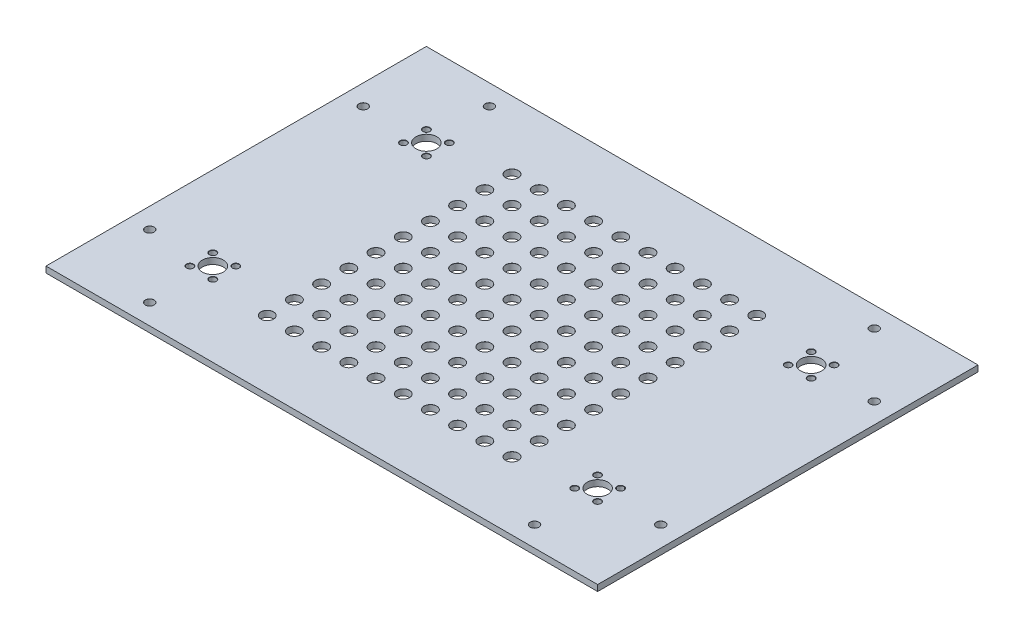
SolidWorks part; units mm, degrees
ref_plane "Front Plane" through (0, 0, 0) normal (0, 0, 1) x (1, 0, 0)
ref_plane "Top Plane" through (0, 0, 0) normal (0, 1, 0) x (1, 0, 0)
ref_plane "Right Plane" through (0, 0, 0) normal (1, 0, 0) x (0, 0, -1)
sketch "Sketch1" plane through (0, 0, 0) normal (0, 1, 0) x (1, 0, 0)
  line L0 (-115.9, 93.7) -> (-115.9, -93.7) construction
  line L1 (-135.9, -93.7) -> (135.9, -93.7)
  line L2 (-135.9, -93.7) -> (-135.9, 93.7)
  line L3 (-135.9, 93.7) -> (135.9, 93.7)
  line L4 (135.9, -93.7) -> (135.9, 93.7)
  line L5 (-135.9, -93.7) -> (135.9, 93.7) construction
  line L6 (-135.9, 93.7) -> (135.9, -93.7) construction
  line L7 (-94.8, -52.6) -> (94.8, -52.6) construction
  line L8 (-94.8, -52.6) -> (-94.8, 52.6) construction
  line L9 (-94.8, 52.6) -> (94.8, 52.6) construction
  line L10 (94.8, -52.6) -> (94.8, 52.6) construction
  line L11 (-94.8, -52.6) -> (94.8, 52.6) construction
  line L12 (-94.8, 52.6) -> (94.8, -52.6) construction
  line L13 (-115.9, 73.7) -> (-73.7, 73.7) construction
  line L14 (-115.9, 73.7) -> (-115.9, 31.5) construction
  line L15 (-115.9, 31.5) -> (-73.7, 31.5) construction
  line L16 (-73.7, 73.7) -> (-73.7, 31.5) construction
  line L17 (-115.9, 73.7) -> (-73.7, 31.5) construction
  line L18 (-115.9, 31.5) -> (-73.7, 73.7) construction
  line L19 (-115.9, 73.7) -> (135.9, 73.7) construction
  line L20 (-135.9, 73.7) -> (-115.9, 73.7) construction
  line L21 (-94.8, 73.7) -> (-94.8, 93.7) construction
  line L22 (-115.9, 52.6) -> (-135.9, 52.6) construction
  line L23 (-60.3, 93.7) -> (-60.3, -93.7) construction
  line L24 (-115.9, -73.7) -> (-73.7, -73.7) construction
  line L25 (-115.9, -73.7) -> (-115.9, -31.5) construction
  line L26 (-115.9, -31.5) -> (-73.7, -31.5) construction
  line L27 (-73.7, -73.7) -> (-73.7, -31.5) construction
  line L28 (-115.9, -73.7) -> (-73.7, -31.5) construction
  line L29 (-115.9, -31.5) -> (-73.7, -73.7) construction
  line L30 (73.7, 73.7) -> (115.9, 73.7) construction
  line L31 (73.7, 73.7) -> (73.7, 31.5) construction
  line L32 (73.7, 31.5) -> (115.9, 31.5) construction
  line L33 (115.9, 73.7) -> (115.9, 31.5) construction
  line L34 (73.7, 73.7) -> (115.9, 31.5) construction
  line L35 (73.7, 31.5) -> (115.9, 73.7) construction
  line L36 (73.7, -31.5) -> (115.9, -31.5) construction
  line L37 (73.7, -31.5) -> (73.7, -73.7) construction
  line L38 (73.7, -73.7) -> (115.9, -73.7) construction
  line L39 (115.9, -31.5) -> (115.9, -73.7) construction
  line L40 (73.7, -31.5) -> (115.9, -73.7) construction
  line L41 (73.7, -73.7) -> (115.9, -31.5) construction
  line L42 (-60.3, 60.3) -> (-60.3, 46.9) construction
  line L43 (-60.3, 60.3) -> (-46.9, 60.3) construction
  circle A0 centre (-94.8, 52.6) radius 5.15
  circle A1 centre (-94.8, -52.6) radius 5.15
  circle A2 centre (94.8, -52.6) radius 5.15
  circle A3 centre (94.8, 52.6) radius 5.15
  circle A4 centre (-60.3, 60.3) radius 1.6 construction
  point P0 (0, 0)
  point P6 (0, 0)
  point P37 (-60.3, 46.9)
  point P39 (-60.3, 60.3)
  point P40 (-60.3, 33.5)
  point P41 (-60.3, 20.1)
  point P42 (-60.3, 6.7)
  point P43 (-60.3, -6.7)
  point P44 (-60.3, -20.1)
  point P45 (-60.3, -33.5)
  point P46 (-60.3, -46.9)
  point P47 (-60.3, -60.3)
  point P53 (-46.9, 60.3)
  point P54 (-46.9, 46.9)
  point P55 (-46.9, 33.5)
  point P56 (-46.9, 20.1)
  point P57 (-46.9, 6.7)
  point P58 (-46.9, -6.7)
  point P59 (-46.9, -20.1)
  point P60 (-46.9, -33.5)
  point P61 (-46.9, -46.9)
  point P62 (-46.9, -60.3)
  point P63 (-33.5, 60.3)
  point P64 (-33.5, 46.9)
  point P65 (-33.5, 33.5)
  point P66 (-33.5, 20.1)
  point P67 (-33.5, 6.7)
  point P68 (-33.5, -6.7)
  point P69 (-33.5, -20.1)
  point P70 (-33.5, -33.5)
  point P71 (-33.5, -46.9)
  point P72 (-33.5, -60.3)
  point P73 (-20.1, 60.3)
  point P74 (-20.1, 46.9)
  point P75 (-20.1, 33.5)
  point P76 (-20.1, 20.1)
  point P77 (-20.1, 6.7)
  point P78 (-20.1, -6.7)
  point P79 (-20.1, -20.1)
  point P80 (-20.1, -33.5)
  point P81 (-20.1, -46.9)
  point P82 (-20.1, -60.3)
  point P83 (-6.7, 60.3)
  point P84 (-6.7, 46.9)
  point P85 (-6.7, 33.5)
  point P86 (-6.7, 20.1)
  point P87 (-6.7, 6.7)
  point P88 (-6.7, -6.7)
  point P89 (-6.7, -20.1)
  point P90 (-6.7, -33.5)
  point P91 (-6.7, -46.9)
  point P92 (-6.7, -60.3)
  point P93 (6.7, 60.3)
  point P94 (6.7, 46.9)
  point P95 (6.7, 33.5)
  point P96 (6.7, 20.1)
  point P97 (6.7, 6.7)
  point P98 (6.7, -6.7)
  point P99 (6.7, -20.1)
  point P100 (6.7, -33.5)
  point P101 (6.7, -46.9)
  point P102 (6.7, -60.3)
  point P103 (20.1, 60.3)
  point P104 (20.1, 46.9)
  point P105 (20.1, 33.5)
  point P106 (20.1, 20.1)
  point P107 (20.1, 6.7)
  point P108 (20.1, -6.7)
  point P109 (20.1, -20.1)
  point P110 (20.1, -33.5)
  point P111 (20.1, -46.9)
  point P112 (20.1, -60.3)
  point P113 (33.5, 60.3)
  point P114 (33.5, 46.9)
  point P115 (33.5, 33.5)
  point P116 (33.5, 20.1)
  point P117 (33.5, 6.7)
  point P118 (33.5, -6.7)
  point P119 (33.5, -20.1)
  point P120 (33.5, -33.5)
  point P121 (33.5, -46.9)
  point P122 (33.5, -60.3)
  point P123 (46.9, 60.3)
  point P124 (46.9, 46.9)
  point P125 (46.9, 33.5)
  point P126 (46.9, 20.1)
  point P127 (46.9, 6.7)
  point P128 (46.9, -6.7)
  point P129 (46.9, -20.1)
  point P130 (46.9, -33.5)
  point P131 (46.9, -46.9)
  point P132 (46.9, -60.3)
  point P133 (60.3, 60.3)
  point P134 (60.3, 46.9)
  point P135 (60.3, 33.5)
  point P136 (60.3, 20.1)
  point P137 (60.3, 6.7)
  point P138 (60.3, -6.7)
  point P139 (60.3, -20.1)
  point P140 (60.3, -33.5)
  point P141 (60.3, -46.9)
  point P142 (60.3, -60.3)
  dimension "D11" = 10.3
  dimension "D12" = 3.2
  dimension "D1" = 42.2
  dimension "D2" = 20
  dimension "D3" = 13.4
  dimension "D6" = 13.4
  dimension "D7" = 13.4
  dimension "D8" = 13.4
  dimension "D9" = 13.4
  dimension "D10" = 13.4
  dimension "PlungerplateWidth" = 271.8
  dimension "PlungerplateHeight" = 187.4
  dimension "D4" = 10
  dimension "D5" = 10
extrude "Boss-Extrude1" add sketch "Sketch1" along normal blind 3
hole_wizard "M3 Clearance Hole1" positions "Sketch11" profile "Sketch13" hole size "M3" standard "DIN" end condition through all
sketch "Sketch11" plane through (0, 3, 0) normal (0, 1, 0) x (1, 0, 0)
  line L1 (-100.455, 58.255) -> (-89.145, 58.255)
  line L2 (-100.455, 58.255) -> (-100.455, 46.945)
  line L3 (-100.455, 46.945) -> (-89.145, 46.945)
  line L4 (-89.145, 58.255) -> (-89.145, 46.945)
  line L5 (-100.455, 58.255) -> (-89.145, 46.945) construction
  line L6 (-100.455, 46.945) -> (-89.145, 58.255) construction
  line L7 (0, 0) -> (0, 50000) construction
  line L8 (0, 0) -> (50000, 0) construction
  line L9 (-100.455, -46.945) -> (-89.145, -58.255) construction
  line L10 (-100.455, -58.255) -> (-89.145, -46.945) construction
  line L11 (-89.145, -58.255) -> (-89.145, -46.945)
  line L12 (-100.455, -46.945) -> (-89.145, -46.945)
  line L13 (-100.455, -58.255) -> (-100.455, -46.945)
  line L14 (-100.455, -58.255) -> (-89.145, -58.255)
  line L15 (100.455, -58.255) -> (89.145, -46.945) construction
  line L16 (100.455, -46.945) -> (89.145, -58.255) construction
  line L17 (100.455, 46.945) -> (89.145, 58.255) construction
  line L18 (100.455, 58.255) -> (89.145, 46.945) construction
  line L19 (100.455, -58.255) -> (89.145, -58.255)
  line L20 (100.455, -58.255) -> (100.455, -46.945)
  line L21 (100.455, -46.945) -> (89.145, -46.945)
  line L22 (89.145, -58.255) -> (89.145, -46.945)
  line L23 (89.145, 58.255) -> (89.145, 46.945)
  line L24 (100.455, 46.945) -> (89.145, 46.945)
  line L25 (100.455, 58.255) -> (100.455, 46.945)
  line L26 (100.455, 58.255) -> (89.145, 58.255)
  point P2 (-89.145, 46.945)
  point P207 (-100.455, 58.255)
  point P208 (-100.455, 46.945)
  point P209 (-89.145, 58.255)
  point P223 (-94.8, 52.6)
  point P235 (-89.145, -58.255)
  point P236 (-100.455, -46.945)
  point P237 (-100.455, -58.255)
  point P238 (-89.145, -46.945)
  point P247 (89.145, -46.945)
  point P248 (100.455, -58.255)
  point P249 (100.455, -46.945)
  point P250 (89.145, -58.255)
  point P251 (89.145, 58.255)
  point P252 (100.455, 46.945)
  point P253 (100.455, 58.255)
  point P254 (89.145, 46.945)
  dimension "D1" = 11.31
sketch "Sketch13" plane through (-89.145, 3, -46.945) normal (1, 0, 0) x (0, 0, 1)
  line L0 (0, 0) -> (0, 3)
  line L1 (0, 3) -> (1.6, 3)
  line L2 (1.6, 3) -> (1.6, 0.125)
  line L3 (1.6, 0.125) -> (1.725, 0)
  line L5 (1.725, 0) -> (0, 0)
  line L6 (-1.6, 0.125) -> (-1.725, 0) construction
  line L11 (0, -6.35) -> (0, 107.95) construction
  dimension "Thru Hole Dia." = 3.2
  dimension "Thru Hole Depth" = 3
  dimension "Near C'Sink Dia." = 3.45
  dimension "Near C'Sink Angle" = 90
hole_wizard "M4 Clearance Hole2" positions "Sketch14" profile "Sketch15" hole size "M4" standard "DIN" end condition through all
sketch "Sketch14" plane through (0, 3, 0) normal (0, 1, 0) x (1, 0, 0)
  line L0 (-135.9, -93.7) -> (-135.9, 93.7) construction
  line L1 (-135.9, 93.7) -> (135.9, 93.7) construction
  line L2 (-94.8, 52.6) -> (94.8, 52.6) construction
  line L3 (-94.8, -52.6) -> (-94.8, 52.6) construction
  line L4 (0, 0) -> (50000, 0) construction
  line L5 (-135.9, -93.7) -> (135.9, 93.7) construction
  line L6 (0, 0) -> (0, -50000) construction
  point P0 (-94.8, 83.7)
  point P1 (-125.9, 52.6)
  point P17 (0, 0)
  point P21 (-125.9, -52.6)
  point P22 (-94.8, -83.7)
  point P23 (94.8, -83.7)
  point P24 (125.9, -52.6)
  point P25 (125.9, 52.6)
  point P26 (94.8, 83.7)
  dimension "D1" = 10
  dimension "D2" = 10
sketch "Sketch15" plane through (-94.8, 3, -83.7) normal (1, 0, 0) x (0, 0, 1)
  line L0 (0, 0) -> (0, 3)
  line L1 (0, 3) -> (2.15, 3)
  line L2 (2.15, 3) -> (2.15, 0.025)
  line L3 (2.15, 0.025) -> (2.175, 0)
  line L5 (2.175, 0) -> (0, 0)
  line L6 (-2.15, 0.025) -> (-2.175, 0) construction
  line L11 (0, -6.35) -> (0, 107.95) construction
  dimension "Thru Hole Dia." = 4.3
  dimension "Thru Hole Depth" = 3
  dimension "Near C'Sink Dia." = 4.35
  dimension "Near C'Sink Angle" = 90
hole_wizard "Ø6.2 (6.2) Diameter Hole1" positions "Sketch16" profile "Sketch17" hole size "Ø6.2" standard "DIN" end condition through all
sketch "Sketch16" plane through (0, 3, 0) normal (0, 1, 0) x (1, 0, 0)
  point P0 (-60.3, 60.3)
  point P9 (-46.9, 60.3)
  point P10 (-33.5, 60.3)
  point P11 (-20.1, 60.3)
  point P12 (-6.7, 60.3)
  point P13 (6.7, 60.3)
  point P14 (20.1, 60.3)
  point P15 (33.5, 60.3)
  point P16 (46.9, 60.3)
  point P17 (60.3, 60.3)
  point P18 (-46.9, 46.9)
  point P19 (-33.5, 46.9)
  point P20 (-20.1, 46.9)
  point P21 (-6.7, 46.9)
  point P22 (6.7, 46.9)
  point P23 (20.1, 46.9)
  point P24 (33.5, 46.9)
  point P25 (46.9, 46.9)
  point P26 (60.3, 46.9)
  point P27 (-46.9, 33.5)
  point P28 (-33.5, 33.5)
  point P29 (-20.1, 33.5)
  point P30 (-6.7, 33.5)
  point P31 (6.7, 33.5)
  point P32 (20.1, 33.5)
  point P33 (33.5, 33.5)
  point P34 (46.9, 33.5)
  point P35 (60.3, 33.5)
  point P36 (-46.9, 20.1)
  point P37 (-33.5, 20.1)
  point P38 (-20.1, 20.1)
  point P39 (-6.7, 20.1)
  point P40 (6.7, 20.1)
  point P41 (20.1, 20.1)
  point P42 (33.5, 20.1)
  point P43 (46.9, 20.1)
  point P44 (60.3, 20.1)
  point P45 (-46.9, 6.7)
  point P46 (-33.5, 6.7)
  point P47 (-20.1, 6.7)
  point P48 (-6.7, 6.7)
  point P49 (6.7, 6.7)
  point P50 (20.1, 6.7)
  point P51 (33.5, 6.7)
  point P52 (46.9, 6.7)
  point P53 (60.3, 6.7)
  point P54 (-46.9, -6.7)
  point P55 (-33.5, -6.7)
  point P56 (-20.1, -6.7)
  point P57 (-6.7, -6.7)
  point P58 (6.7, -6.7)
  point P59 (20.1, -6.7)
  point P60 (33.5, -6.7)
  point P61 (46.9, -6.7)
  point P62 (60.3, -6.7)
  point P63 (-46.9, -20.1)
  point P64 (-33.5, -20.1)
  point P65 (-20.1, -20.1)
  point P66 (-6.7, -20.1)
  point P67 (6.7, -20.1)
  point P68 (20.1, -20.1)
  point P69 (33.5, -20.1)
  point P70 (46.9, -20.1)
  point P71 (60.3, -20.1)
  point P72 (-46.9, -33.5)
  point P73 (-33.5, -33.5)
  point P74 (-20.1, -33.5)
  point P75 (-6.7, -33.5)
  point P76 (6.7, -33.5)
  point P77 (20.1, -33.5)
  point P78 (33.5, -33.5)
  point P79 (46.9, -33.5)
  point P80 (60.3, -33.5)
  point P81 (-46.9, -46.9)
  point P82 (-33.5, -46.9)
  point P83 (-20.1, -46.9)
  point P84 (-6.7, -46.9)
  point P85 (6.7, -46.9)
  point P86 (20.1, -46.9)
  point P87 (33.5, -46.9)
  point P88 (46.9, -46.9)
  point P89 (60.3, -46.9)
  point P90 (-46.9, -60.3)
  point P91 (-33.5, -60.3)
  point P92 (-20.1, -60.3)
  point P93 (-6.7, -60.3)
  point P94 (6.7, -60.3)
  point P95 (20.1, -60.3)
  point P96 (33.5, -60.3)
  point P97 (46.9, -60.3)
  point P98 (60.3, -60.3)
  point P99 (-60.3, 46.9)
  point P100 (-60.3, 33.5)
  point P101 (-60.3, 20.1)
  point P102 (-60.3, 6.7)
  point P103 (-60.3, -6.7)
  point P104 (-60.3, -20.1)
  point P105 (-60.3, -33.5)
  point P106 (-60.3, -46.9)
  point P107 (-60.3, -60.3)
  dimension "D1" = 10
  dimension "D2" = 10
sketch "Sketch17" plane through (-60.3, 3, -60.3) normal (1, 0, 0) x (0, 0, 1)
  line L0 (0, 0) -> (0, 3)
  line L1 (0, 3) -> (3.1, 3)
  line L2 (3.1, 3) -> (3.1, 0.025)
  line L3 (3.1, 0.025) -> (3.125, 0)
  line L5 (3.125, 0) -> (0, 0)
  line L6 (-3.1, 0.025) -> (-3.125, 0) construction
  line L11 (0, -6.35) -> (0, 107.95) construction
  dimension "Thru Hole Dia." = 6.2
  dimension "Thru Hole Depth" = 3
  dimension "Near C'Sink Dia." = 6.25
  dimension "Near C'Sink Angle" = 90
equation "\"D7@Sketch1\"=\"D6@Sketch1\""
equation "\"D10@Sketch1\"=\"D9@Sketch1\""
equation "\"D3@Sketch1\"=\"D9@Sketch1\""
